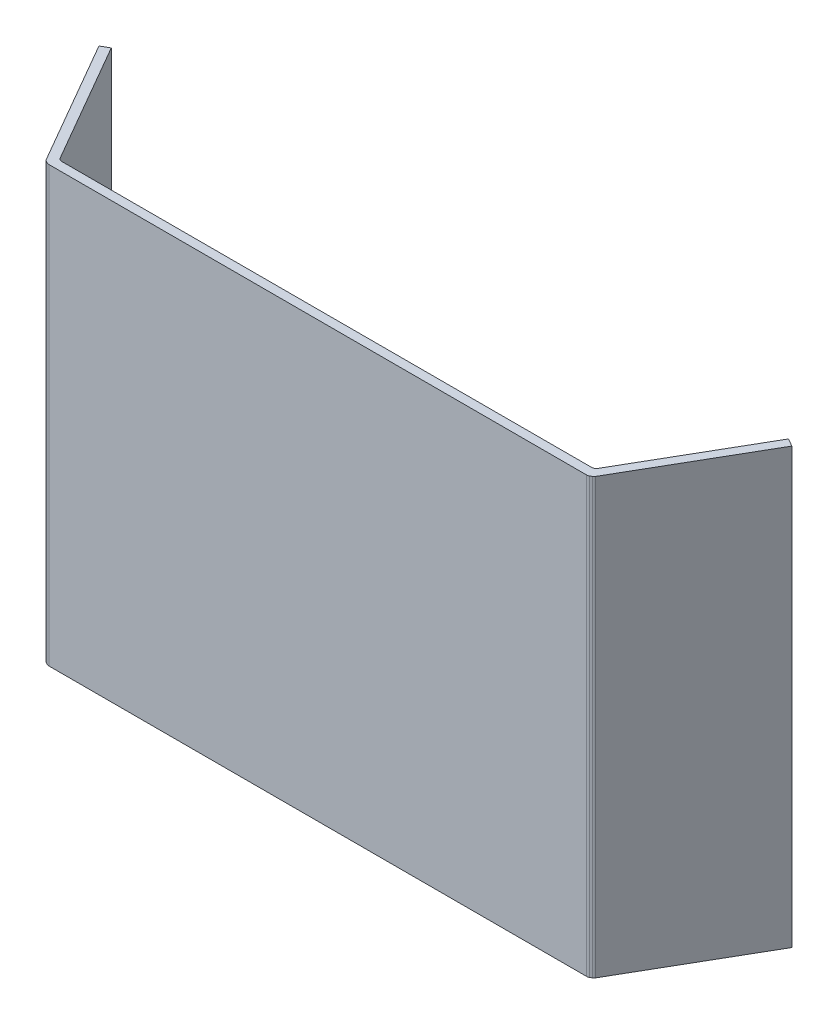
SolidWorks part; units mm, degrees
ref_plane "Front Plane" through (0, 0, 0) normal (0, 0, 1) x (1, 0, 0)
ref_plane "Top Plane" through (0, 0, 0) normal (0, 1, 0) x (1, 0, 0)
ref_plane "Right Plane" through (0, 0, 0) normal (1, 0, 0) x (0, 0, -1)
sketch "Sketch1" plane through (0, 0, 0) normal (0, 1, 0) x (1, 0, 0)
  line L0 (0, 1.5875) -> (0, 63.324) construction
  line L1 (94.7976, -1.5875) -> (-94.7976, -1.5875)
  line L3 (93.881, 1.5875) -> (-93.881, 1.5875)
  line L4 (120.1976, 43.9941) -> (94.7976, 0) construction
  line L5 (94.7976, -1.5875) -> (-94.7976, 1.5875) construction
  line L6 (94.7976, 1.5875) -> (-94.7976, -1.5875) construction
  line L7 (104.3226, 16.4978) -> (-104.3226, 16.4978) construction
  line L8 (-94.7976, 0) -> (-132.8976, 65.9911) construction
  line L9 (94.7976, 0) -> (132.8976, 65.9911) construction
  line L10 (-94.7976, 0) -> (94.7976, 0) construction
  line L11 (-118.8227, 44.7878) -> (-93.881, 1.5875)
  line L12 (-118.8227, 44.7878) -> (-121.5724, 43.2003)
  line L13 (93.4227, 0.7938) -> (121.5724, 43.2003) construction
  line L14 (-121.5724, 43.2003) -> (-96.1724, -0.7937)
  line L15 (-118.8227, 44.7878) -> (-96.1724, -0.7937) construction
  line L16 (-93.4227, 0.7938) -> (-121.5724, 43.2003) construction
  line L17 (-120.1976, 43.9941) -> (-94.7976, 0) construction
  line L18 (-94.7976, -1.5875) -> (-96.1724, -0.7937)
  line L19 (118.8227, 44.7878) -> (96.1724, -0.7937) construction
  line L20 (94.7976, 0) -> (132.8976, 65.9911) construction
  line L21 (94.7976, -1.5875) -> (96.1724, -0.7937)
  line L22 (121.5724, 43.2003) -> (96.1724, -0.7937)
  line L23 (118.8227, 44.7878) -> (121.5724, 43.2003)
  line L24 (118.8227, 44.7878) -> (93.881, 1.5875)
  point P0 (0, 0)
  point P11 (0, 16.4978)
  point P16 (-107.4976, 21.997)
  point P28 (107.4976, 21.997)
  dimension "D1" = 3.175
  dimension "D2" = 3.175
  dimension "D3" = 208.6451
  dimension "D4" = 120
  dimension "D5" = 19.05
  dimension "D6" = 50.8
  dimension "D7" = 76.2
extrude "Boss-Extrude1" add sketch "Sketch1" along normal blind 152.4
fillet "Fillet1" radius 1.5875 6 edges at (93.881, 76.2, -1.5875) (-93.881, 76.2, -1.5875) (-94.7976, 76.2, 1.5875) (-96.1724, 76.2, 0.7937) (94.7976, 76.2, 1.5875) (96.1724, 76.2, 0.7937)
sketch "Sketch2" plane through (-72.473, 0, 41.8423) normal (-0.866, 0, 0.5) x (0.5, 0, 0.866)
  line L0 (-47.8242, 0) -> (-98.1988, 101.6)
  line L1 (-47.8242, 0) -> (-47.8242, 152.4) construction
  line L2 (-98.1988, 152.4) -> (-98.1988, 0) construction
  line L3 (-98.1988, 101.6) -> (-98.1988, 0)
  line L4 (-98.1988, 0) -> (-47.8242, 0)
  line L5 (-98.1988, 152.4) -> (-47.8242, 152.4) construction
  dimension "D1" = 50.8
extrude "Cut-Extrude1" [suppressed] cut sketch "Sketch2" against normal through all
fillet "Fillet2" [suppressed] radius 1.5875
sketch "Sketch3" plane through (72.473, 0, 41.8423) normal (0.866, 0, 0.5) x (0.5, 0, -0.866)
  line L0 (47.8242, 0) -> (98.1988, 101.6)
  line L1 (98.1988, 152.4) -> (98.1988, 0) construction
  line L2 (98.1988, 101.6) -> (98.1988, 0)
  line L3 (98.1988, 0) -> (47.8242, 0)
  line L4 (47.8242, 152.4) -> (98.1988, 152.4) construction
  dimension "D1" = 50.8
extrude "Cut-Extrude2" [suppressed] cut sketch "Sketch3" against normal through all
